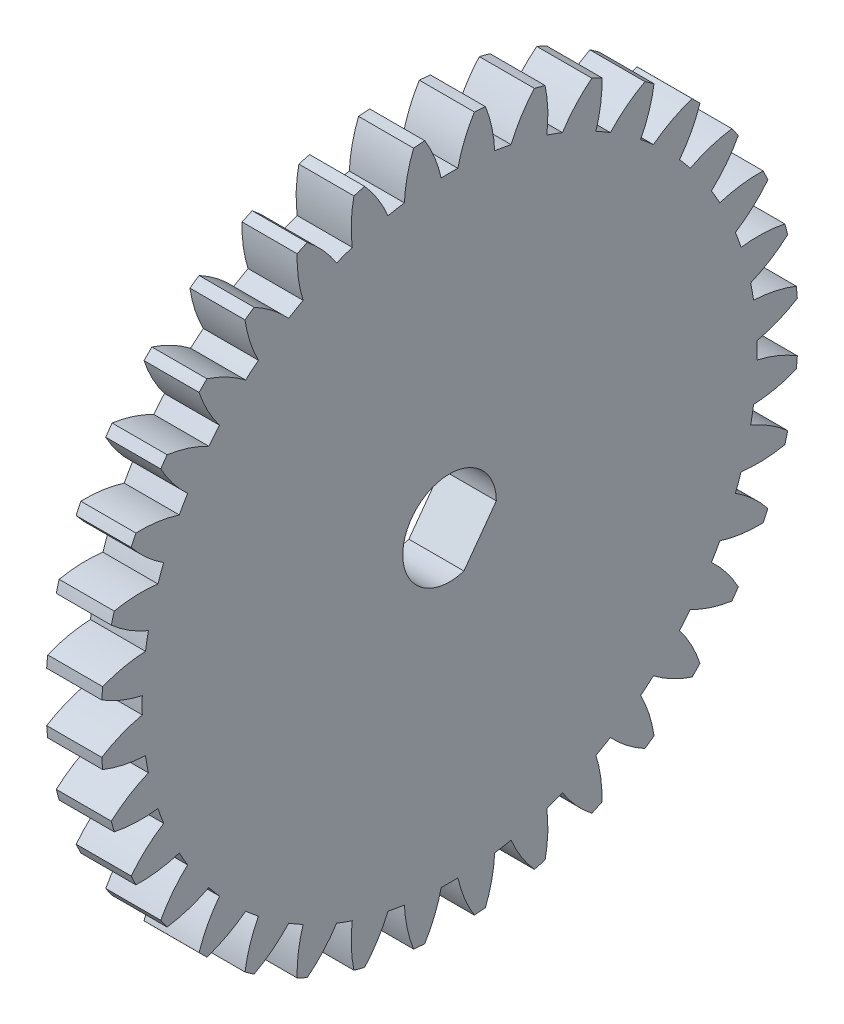
SolidWorks part; units mm, degrees
ref_plane "Plane1" through (0, 0, 0) normal (0, 0, 1) x (1, 0, 0)
ref_plane "Plane2" through (0, 0, 0) normal (0, 1, 0) x (1, 0, 0)
ref_plane "Plane3" through (0, 0, 0) normal (1, 0, 0) x (0, 0, -1)
sketch "HoldingSke" plane through (0, 0, 0) normal (0, 1, 0) x (1, 0, 0)
  line L0 (0, 0) -> (0.809, -0.5878)
  line L1 (-15, 0) -> (100, 0) construction
  line L2 (0, 0) -> (-2.1039, 2.3779)
  line L3 (0, 0) -> (-11.863, 4.5341)
  line L4 (0, 0) -> (6.9867, 5.0761)
  line L5 (0, 0) -> (-46.8476, -17.4728)
  line L6 (0, 0) -> (-2.4869, -1.6779)
  line L7 (-2.1039, 2.3779) -> (8.6586, 51.2059)
  line L8 (-76.2, 54.61) -> (-76.1, 54.61)
  line L9 (-71.009, 38.7566) -> (-53.1078, 45.2721)
  line L10 (-76.2, 71.12) -> (104.1128, 71.12)
  line L11 (0, 0) -> (-3, 0)
  line L12 (-76.2, 101.6) -> (-76.162, 101.6)
  line L13 (24.9733, 27.94) -> (52.9518, 28.4284)
  line L14 (24.9733, 27.94) -> (24.9743, 27.94)
  line L15 (24.9733, 27.94) -> (100.4006, 29.5858)
  line L16 (-63.627, -1) -> (-12.827, -1)
  circle A0 centre (0, 0) radius 0.4
  circle A1 centre (0, 0) radius 16.749
  circle A2 centre (0, 0) radius 37.5
  circle A3 centre (0, 0) radius 0.4
  dimension "MHD" = 33.498
  dimension "Hub_dia" = 75
  dimension "Bore" = 0.8
  dimension "MBD" = 0.8
  dimension "Num_teeth" = 36
  dimension "Pitch" = 1
  dimension "Overall_len" = 50
  dimension "Show_teeth" = 36
  dimension "Thickness" = 3
  dimension "OAL" = 50.0001
  dimension "T_dim" = 0.1
  dimension "Ap" = 20
  dimension "H" = 19.05
  dimension "Pitch_radius" = 180.3128
  dimension "Width" = 3
  dimension "Backlash" = 0.038
  dimension "Addendum_fac" = 1
  dimension "Dedendum_fac" = 1.25
  dimension "Clearance_fac" = 0.25
  dimension "Dedendum_add" = 0.001
  dimension "Module" = 1
sketch "BasProSke" plane through (0, 0, 0) normal (0, 1, 0) x (1, 0, 0)
  line L0 (-10, 0) -> (60, 0) construction
  line L1 (0, 0) -> (0, 19)
  line L2 (0, 0) -> (3, 0)
  line L3 (3, 0) -> (3, 19)
  line L4 (3, 19) -> (0, 19)
  dimension "Thickness" = 3
  dimension "Diameter" = 38
revolve "Base-Revolve" add sketch "BasProSke" angle 360 about L0
sketch "TooCutSke" plane through (0, 0, 0) normal (1, 0, 0) x (0, 0, -1)
  line L1 (0, 0) -> (0, 107) construction
  line L2 (0, 0) -> (-0.8516, 17.9798) construction
  line L3 (0, 0) -> (-3.1351, 35.8344) construction
  line L4 (-0.8516, 17.9798) -> (-1.5676, 17.9172) construction
  arc A0 (0.4547, 16.7428) -> (-0.4547, 16.7428) centre (0, 0) ccw
  arc A1 (1.3689, 18.9761) -> (-1.3689, 18.9761) centre (0, 0) ccw
  circle A2 centre (0, 0) radius 18 construction
  circle A3 centre (0, 0) radius 16.9145 construction
  arc A4 (-0.4547, 16.7428) -> (-1.3689, 18.9761) centre (-7.4808, 15.1702) ccw
  arc A5 (1.3689, 18.9761) -> (0.4547, 16.7428) centre (7.4808, 15.1702) ccw
  dimension "Root_dia" = 33.498
  dimension "Overcut_dia" = 38.0508
  dimension "Pitch_dia" = 36
  dimension "Base_dia" = 33.8289
  dimension "Flank_rad" = 7.2
  dimension "Half_ang" = 5
  dimension "Half_CT" = 0.7186
extrude "ToothCut" cut sketch "TooCutSke" along normal through all
fillet "Breaks" [suppressed] radius 0.02
fillet "RootFillets" [suppressed] radius 0.251
pattern_circular "TeethCuts" count 36 every 10 about axis through (-10, 0, 0) along (1, 0, 0) of "ToothCut", "RootFillets", "Breaks"
sketch "HubNeaOneSke" plane through (0, 0, 0) normal (-1, 0, 0) x (0, 0, 1)
  circle A0 centre (0, 0) radius 16.749
  dimension "Diameter" = 33.498
extrude "HubNearOne" [suppressed] add sketch "HubNeaOneSke" along normal blind 47.0001
sketch "HubNeaBotSke" plane through (0, 0, 0) normal (-1, 0, 0) x (0, 0, 1)
  circle A0 centre (0, 0) radius 16.749
  dimension "Diameter" = 33.498
extrude "HubNearBoth" [suppressed] add sketch "HubNeaBotSke" along normal blind 23.5
ref_plane "FarPln" through (3, 0, 0) normal (1, 0, 0) x (0, 0, -1)
sketch "HubFarSke" plane through (3, 0, 0) normal (1, 0, 0) x (0, 0, -1)
  circle A0 centre (0, 0) radius 16.749
  dimension "Diameter" = 33.498
extrude "HubFar" [suppressed] add sketch "HubFarSke" along normal blind 23.5
sketch "BorSke" plane through (0, 0, 0) normal (1, 0, 0) x (0, 0, -1)
  circle A0 centre (0, 0) radius 0.4
  dimension "Diameter" = 0.8
extrude "Bore" cut sketch "BorSke" along normal mid plane 100.0001
sketch "KeySke" plane through (0, 0, 0) normal (1, 0, 0) x (0, 0, -1)
  line L0 (-0.05, 0) -> (-0.05, 0.5)
  line L1 (-0.05, 0.5) -> (0.05, 0.5)
  line L2 (0.05, 0.5) -> (0.05, 0)
  line L3 (0, 0) -> (0, 34) construction
  line L4 (-0.05, 0) -> (0.05, 0)
  dimension "Offset" = 0.5
  dimension "Width" = 0.1
extrude "Keyway" [suppressed] cut sketch "KeySke" along normal mid plane 100.0001
pattern_circular "Keyway2" [suppressed] count 2 every 90 about axis through (-10, 0, 0) along (1, 0, 0)
sketch "Sketch2" plane through (0, 0, 0) normal (-1, 0, 0) x (0, 0, 1)
  line L0 (-2.55, 0) -> (-0.7853, -2.4261)
  arc A0 (-0.7853, -2.4261) -> (-2.55, 0) centre (0, 0) ccw
extrude "Cut-Extrude2" cut sketch "Sketch2" against normal through all
equation "' \"Module@HoldingSke\" = 6.35"
equation "' \"Num_teeth@HoldingSke\" = 12"
equation "' \"Ap@HoldingSke\" =  20"
equation "' \"Ap@HoldingSke\" = 20"
equation "' \"Width@HoldingSke\" = 0.5 * 25.4"
equation "' \"Hub_dia@HoldingSke\"= 1 * 25.4"
equation "' \"Hub_dia@HoldingSke\" = 1 * 25.4"
equation "' \"Overall_len@HoldingSke\" = 1.0 * 25.4"
equation "' \"Bore@HoldingSke\" = 0.75 * 25.4"
equation "' \"T_dim@HoldingSke\" = 0.1 * 25.4"
equation "' \"Width@KeySke\" = 0.25 * 25.4"
equation "' \"Show_teeth@HoldingSke\" = 13"
equation "' \"Backlash@HoldingSke\" = 0.009 * 25.4"
equation "' \"Addendum_fac@HoldingSke\" = 1.0"
equation "' \"Dedendum_fac@HoldingSke\" = 1.25"
equation "' \"Dedendum_add@HoldingSke\" = 0.00005 * 25.4"
equation "' \"Clearance_fac@HoldingSke\" = 0.25"
equation "\"Pitch@HoldingSke\" = 1 / \"Module@HoldingSke\""
equation "\"Overcut_dia@TooCutSke\" = (\"Num_teeth@HoldingSke\" + 2 * \"Addendum_fac@HoldingSke\") / \"Pitch@HoldingSke\" + 0.002 * 25.4"
equation "\"Pitch_dia@TooCutSke\" = \"Num_teeth@HoldingSke\" / \"Pitch@HoldingSke\""
equation "\"Base_dia@TooCutSke\" = \"Num_teeth@HoldingSke\" / \"Pitch@HoldingSke\" * cos((\"Ap@HoldingSke\"  * 3.14159265 / 180))"
equation "\"Root_dia@TooCutSke\" = (\"Num_teeth@HoldingSke\" + 2) / \"Pitch@HoldingSke\" - 2 * (\"Addendum_fac@HoldingSke\" + \"Dedendum_fac@HoldingSke\") / \"Pitch@HoldingSke\" - \"Dedendum_add@HoldingSke\" * 2"
equation "\"Half_ang@TooCutSke\" = 180 / \"Num_teeth@HoldingSke\""
equation "\"Half_CT@TooCutSke\" = \"Num_teeth@HoldingSke\" / \"Pitch@HoldingSke\" * sin((3.14159265 / 2 / \"Num_teeth@HoldingSke\")) / 2 - 7 * \"Backlash@HoldingSke\" / 4"
equation "\"Flank_rad@TooCutSke\" = \"Num_teeth@HoldingSke\" / \"Pitch@HoldingSke\" / 5"
equation "\"Radius@RootFillets\" = \"Clearance_fac@HoldingSke\" / \"Pitch@HoldingSke\" + \"Dedendum_add@HoldingSke\""
equation "\"Break_rad@Breaks\" = 0.02 / \"Pitch@HoldingSke\""
equation "\"Thickness@HoldingSke\" = \"Width@HoldingSke\""
equation "\"OAL@HoldingSke\" = \"Thickness@HoldingSke\""
equation "\"MHD@HoldingSke\" = (\"Num_teeth@HoldingSke\" + 2) / \"Pitch@HoldingSke\" - 2 * (\"Addendum_fac@HoldingSke\" + \"Dedendum_fac@HoldingSke\")  / \"Pitch@HoldingSke\" - \"Dedendum_add@HoldingSke\" * 2"
equation "\"MBD@HoldingSke\" = (\"Num_teeth@HoldingSke\" + 2) / \"Pitch@HoldingSke\" - 2 * (\"Addendum_fac@HoldingSke\" + \"Dedendum_fac@HoldingSke\")  / \"Pitch@HoldingSke\" - \"Dedendum_add@HoldingSke\" * 2 - 0.002 * 25.4"
equation "\"MHD@HoldingSke\" = ((sgn( \"MHD@HoldingSke\" - \"Hub_dia@HoldingSke\" )-1)*( \"MHD@HoldingSke\" - \"Hub_dia@HoldingSke\" ))/-2+ \"Hub_dia@HoldingSke\""
equation "\"MBD@HoldingSke\" = ((sgn( \"MBD@HoldingSke\" - \"Bore@HoldingSke\" )-1)*( \"MBD@HoldingSke\" - \"Bore@HoldingSke\" ))/-2+ \"Bore@HoldingSke\""
equation "\"OAL@HoldingSke\" = ((sgn( \"OAL@HoldingSke\" - \"Overall_len@HoldingSke\" )+1)*( \"OAL@HoldingSke\" - \"Overall_len@HoldingSke\" ))/2 + \"Overall_len@HoldingSke\" + 0.000002 * 25.4"
equation "\"Num_teeth@TeethCuts\" = int( \"Show_teeth@HoldingSke\" ) + 1"
equation "\"Num_teeth@TeethCuts\" = ((sgn( \"Num_teeth@TeethCuts\" - \"Num_teeth@HoldingSke\" )-1)*( \"Num_teeth@TeethCuts\" - \"Num_teeth@HoldingSke\" ))/-2+ \"Num_teeth@HoldingSke\""
equation "\"Num_teeth@TeethCuts\" = ((sgn( \"Num_teeth@TeethCuts\" - 2.0)+1)*( \"Num_teeth@TeethCuts\" - 2.0))/2 +2.0"
equation "\"Angle@TeethCuts\" = 360.0 / \"Num_teeth@HoldingSke\""
equation "\"Diameter@BasProSke\" = (\"Num_teeth@HoldingSke\" + 2 * \"Addendum_fac@HoldingSke\") / \"Pitch@HoldingSke\""
equation "\"Thickness@BasProSke\"  = \"Thickness@HoldingSke\""
equation "' \"Fillet_rad@BasProSke\" =  \"Thickness@HoldingSke\" * 0.05"
equation "' \"Fillet_rad@BasProSke\" = \"Thickness@HoldingSke\" * 0.05"
equation "\"MHD@HoldingSke\" = ((sgn( \"MHD@HoldingSke\" - \"Root_dia@TooCutSke\" )-1)*( \"MHD@HoldingSke\" - \"Root_dia@TooCutSke\" ))/-2+ \"Root_dia@TooCutSke\""
equation "\"Diameter@HubNeaOneSke\" = \"MHD@HoldingSke\""
equation "\"Length@HubNearOne\" = \"OAL@HoldingSke\" - \"Thickness@BasProSke\""
equation "\"Diameter@HubNeaBotSke\" = \"MHD@HoldingSke\""
equation "\"Length@HubNearBoth\" = ( \"OAL@HoldingSke\" - \"Thickness@BasProSke\" ) / 2.0"
equation "\"Thickness@FarPln\" = \"Thickness@BasProSke\""
equation "\"Diameter@HubFarSke\" = \"MHD@HoldingSke\""
equation "\"Length@HubFar\" = ( \"OAL@HoldingSke\" - \"Thickness@BasProSke\" ) / 2.0"
equation "\"Diameter@BorSke\" = \"MBD@HoldingSke\""
equation "\"D1@Bore\" = \"OAL@HoldingSke\" * 2.0"
equation "\"D1@Keyway\" = \"OAL@HoldingSke\" * 2.0"
equation "\"Offset@KeySke\" = \"T_dim@HoldingSke\" + \"MBD@HoldingSke\" / 2.0"
